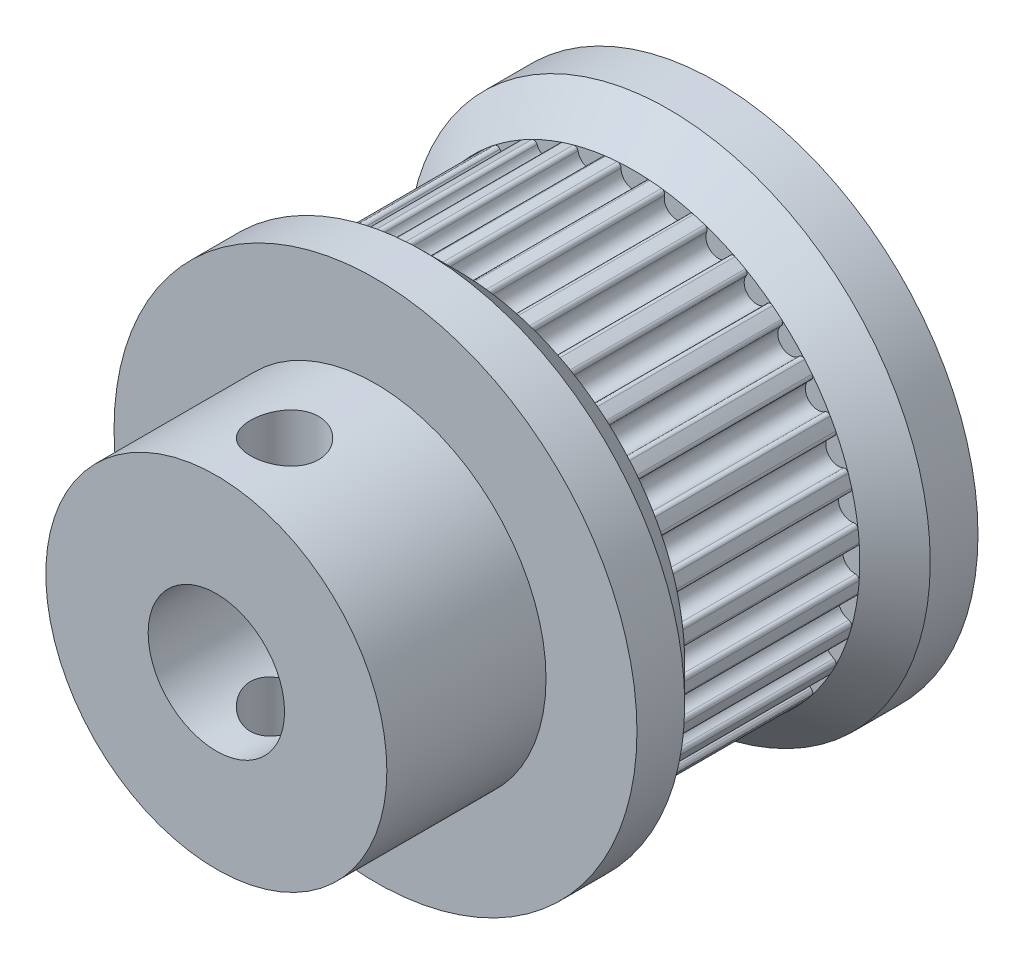
SolidWorks part; units mm, degrees
other "Camera1"
other "Camera2"
other "Camera3"
ref_plane "Front" through (0, 0, 0) normal (0, 0, 1) x (1, 0, 0)
ref_plane "Top" through (0, 0, 0) normal (0, 1, 0) x (1, 0, 0)
ref_plane "Right" through (0, 0, 0) normal (1, 0, 0) x (0, 0, -1)
sketch "Sketch1" plane through (0, 0, 0) normal (1, 0, 0) x (0, 0, -1)
  line L0 (0, 0) -> (-24.4032, 0) construction
  line L4 (-3.65, 9.95) -> (-11.35, 9.95)
  line L5 (-15, 11.5) -> (-15, 3)
  line L6 (-15, 3) -> (0, 3)
  line L7 (0, 3) -> (0, 11.5)
  line L9 (-2.1, 11.5) -> (-3.65, 9.95)
  line L11 (-7.5, 9.95) -> (-7.5, 22.0506) construction
  line L12 (-12.9, 11.5) -> (-11.35, 9.95)
  line L17 (-15, 11.5) -> (-12.9, 11.5)
  line L18 (-2.1, 11.5) -> (0, 11.5)
  dimension "D1" = 135
  dimension "D2" = 15
  dimension "D3" = 7.7
  dimension "D4" = 19.9
  dimension "D5" = 23
  dimension "D8" = 6
revolve "Revolve1" add sketch "Sketch1" angle 360 about L0
ref_plane "Plane2" through (0, 0, 3.65) normal (0, 0, 1) x (1, 0, 0)
ref_plane "Plane3" through (0, 0, 11.35) normal (0, 0, 1) x (1, 0, 0)
sketch "Sketch2" plane through (0, 0, 3.65) normal (0, 0, 1) x (1, 0, 0)
  circle A0 centre (0, 9.75) radius 0.55
  circle A2 centre (1.9021, 9.5627) radius 0.55
  circle A3 centre (3.7312, 9.0078) radius 0.55
  circle A4 centre (5.4168, 8.1068) radius 0.55
  circle A5 centre (6.8943, 6.8943) radius 0.55
  circle A6 centre (8.1068, 5.4168) radius 0.55
  circle A7 centre (9.0078, 3.7312) radius 0.55
  circle A8 centre (9.5627, 1.9021) radius 0.55
  circle A9 centre (9.75, 0) radius 0.55
  circle A10 centre (9.5627, -1.9021) radius 0.55
  circle A11 centre (9.0078, -3.7312) radius 0.55
  circle A12 centre (8.1068, -5.4168) radius 0.55
  circle A13 centre (6.8943, -6.8943) radius 0.55
  circle A14 centre (5.4168, -8.1068) radius 0.55
  circle A15 centre (3.7312, -9.0078) radius 0.55
  circle A16 centre (1.9021, -9.5627) radius 0.55
  circle A17 centre (0, -9.75) radius 0.55
  circle A18 centre (-1.9021, -9.5627) radius 0.55
  circle A19 centre (-3.7312, -9.0078) radius 0.55
  circle A20 centre (-5.4168, -8.1068) radius 0.55
  circle A21 centre (-6.8943, -6.8943) radius 0.55
  circle A22 centre (-8.1068, -5.4168) radius 0.55
  circle A23 centre (-9.0078, -3.7312) radius 0.55
  circle A24 centre (-9.5627, -1.9021) radius 0.55
  circle A25 centre (-9.75, 0) radius 0.55
  circle A26 centre (-9.5627, 1.9021) radius 0.55
  circle A27 centre (-9.0078, 3.7312) radius 0.55
  circle A28 centre (-8.1068, 5.4168) radius 0.55
  circle A29 centre (-6.8943, 6.8943) radius 0.55
  circle A30 centre (-5.4168, 8.1068) radius 0.55
  circle A31 centre (-3.7312, 9.0078) radius 0.55
  circle A32 centre (-1.9021, 9.5627) radius 0.55
  point P68 (0, 0)
  dimension "D1" = 1.1
  dimension "D2" = 9.75
  dimension "D3" = 32
extrude "Cut-Extrude1" cut sketch "Sketch2" along normal up to surface (7.7 mm away) up to plane "Plane3"
fillet "Fillet1" radius 0.16 64 edges at (-5.9506, 7.9745, 7.5) (-5.0902, 8.5494, 7.5) (-7.3921, 6.6603, 7.5) (-6.6603, 7.3921, 7.5) (-8.5494, 5.0902, 7.5) (-7.9745, 5.9506, 7.5) (-9.3782, 3.3245, 7.5) (-8.9822, 4.2806, 7.5) (-9.8466, 1.4311, 7.5) (-9.6447, 2.446, 7.5) (-9.9365, -0.5174, 7.5) (-9.9365, 0.5174, 7.5) (-9.6447, -2.446, 7.5) (-9.8466, -1.4311, 7.5) (-8.9822, -4.2806, 7.5) (-9.3782, -3.3245, 7.5) (-7.9745, -5.9506, 7.5) (-8.5494, -5.0902, 7.5) (-6.6603, -7.3921, 7.5) (-7.3921, -6.6603, 7.5) (-5.0902, -8.5494, 7.5) (-5.9506, -7.9745, 7.5) (-3.3245, -9.3782, 7.5) (-4.2806, -8.9822, 7.5) (-1.4311, -9.8466, 7.5) (-2.446, -9.6447, 7.5) (0.5174, -9.9365, 7.5) (-0.5174, -9.9365, 7.5) (2.446, -9.6447, 7.5) (1.4311, -9.8466, 7.5) (4.2806, -8.9822, 7.5) (3.3245, -9.3782, 7.5) (5.9506, -7.9745, 7.5) (5.0902, -8.5494, 7.5) (7.3921, -6.6603, 7.5) (6.6603, -7.3921, 7.5) (8.5494, -5.0902, 7.5) (7.9745, -5.9506, 7.5) (9.3782, -3.3245, 7.5) (8.9822, -4.2806, 7.5) (9.8466, -1.4311, 7.5) (9.6447, -2.446, 7.5) (9.9365, 0.5174, 7.5) (9.9365, -0.5174, 7.5) (9.6447, 2.446, 7.5) (9.8466, 1.4311, 7.5) (8.9822, 4.2806, 7.5) (9.3782, 3.3245, 7.5) (7.9745, 5.9506, 7.5) (8.5494, 5.0902, 7.5) (6.6603, 7.3921, 7.5) (7.3921, 6.6603, 7.5) (5.0902, 8.5494, 7.5) (5.9506, 7.9745, 7.5) (3.3245, 9.3782, 7.5) (4.2806, 8.9822, 7.5) (1.4311, 9.8466, 7.5) (2.446, 9.6447, 7.5) (-0.5174, 9.9365, 7.5) (0.5174, 9.9365, 7.5) (-2.446, 9.6447, 7.5) (-1.4311, 9.8466, 7.5) (-4.2806, 8.9822, 7.5) (-3.3245, 9.3782, 7.5)
sketch "Sketch3" plane through (0, 0, 15) normal (0, 0, 1) x (1, 0, 0)
  circle A0 centre (0, 0) radius 3
  circle A1 centre (0, 0) radius 7.5
  circle A2 centre (0, 0) radius 3 construction
  dimension "D1" = 15
extrude "Boss-Extrude1" add sketch "Sketch3" along normal blind 7
sketch "Sketch4" plane through (0, 0, 0) normal (0, 1, 0) x (1, 0, 0)
  line L0 (-3, -22) -> (3, -22) construction
  circle A0 centre (0, -19) radius 1.5
  dimension "D2" = 3
  dimension "D1" = 3
extrude "Cut-Extrude2" cut sketch "Sketch4" against normal through all both and the other way through all
scale "Echelle1" scale about centroid uniform scaling yes scale factor 2
scale "Echelle2" scale about centroid uniform scaling yes scale factor 0.25
